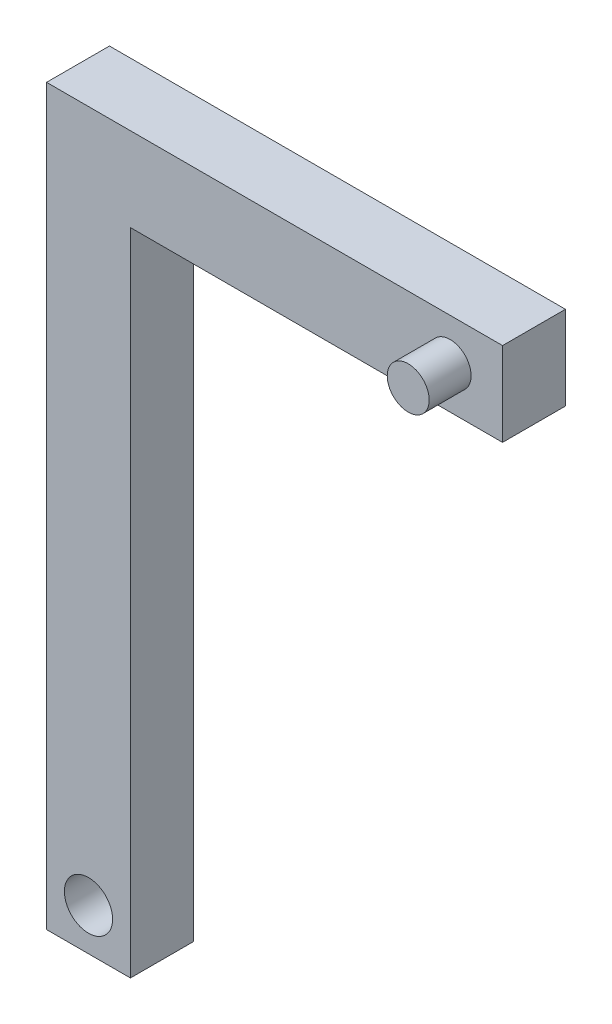
SolidWorks part; units mm, degrees
ref_plane "Alzado" through (0, 0, 0) normal (0, 0, 1) x (1, 0, 0)
ref_plane "Planta" through (0, 0, 0) normal (0, 1, 0) x (1, 0, 0)
ref_plane "Vista lateral" through (0, 0, 0) normal (1, 0, 0) x (0, 0, -1)
sketch "Croquis1" plane through (0, 0, 0) normal (0, 0, 1) x (1, 0, 0)
  line L1 (0, 0) -> (22.5, 0)
  line L2 (0, 0) -> (0, -4)
  line L3 (0, -4) -> (22.5, -4)
  line L4 (22.5, 0) -> (22.5, -4)
  circle A0 centre (3.5, -2) radius 1.05
  dimension "D5" = 2.1
  dimension "D1" = 4
  dimension "D2" = 22.5
  dimension "D3" = 19
  dimension "D4" = 2
extrude "Saliente-Extruir1" add sketch "Croquis1" along normal blind 3 contours L1 L4 L3 L2
sketch "Croquis3" plane through (0, 0, 0) normal (0, 0, -1) x (-1, 0, 0)
  line L0 (0, 0) -> (0, -4) construction
  line L1 (0, 0) -> (-22.5, 0) construction
  circle A0 centre (-20, -2) radius 1
  dimension "D3" = 2
  dimension "D1" = 20
  dimension "D2" = 2
sketch "Croquis4" plane through (0, 0, 3) normal (0, 0, 1) x (1, 0, 0)
  line L0 (0, 0) -> (22.5, 0) construction
  circle A0 centre (2.25, -2) radius 1.05
  dimension "D2" = 2.1
  dimension "D3" = 2
sketch "Croquis5" plane through (0, 0, 0) normal (0, 0, -1) x (-1, 0, 0)
  line L0 (0, -4) -> (-22.5, -4) construction
  line L1 (-4.75, -4) -> (-0.75, -4)
  line L2 (-4.75, -4) -> (-4.75, -35)
  line L3 (-4.75, -35) -> (-0.75, -35)
  line L4 (-0.75, -4) -> (-0.75, -35)
  line L5 (0, 0) -> (-22.5, 0) construction
  circle A2 centre (-2.75, -33) radius 1.05
  dimension "D1" = 2
  dimension "D4" = 2.1
  dimension "D5" = 2
  dimension "D3" = 35
  dimension "D2" = 4
extrude "Saliente-Extruir3" add sketch "Croquis5" against normal blind 3
sketch "Croquis10" plane through (0, 0, 3) normal (0, 0, 1) x (1, 0, 0)
  line L1 (0.75, -4) -> (-0.4142, -4)
  line L2 (0.75, -4) -> (0.75, 0.5775)
  line L3 (0.75, 0.5775) -> (-0.4142, 0.5775)
  line L4 (-0.4142, -4) -> (-0.4142, 0.5775)
extrude "Cortar-Extruir4" cut sketch "Croquis10" against normal through all
extrude "Saliente-Extruir4" add sketch "Croquis3" against normal blind 5
sketch "Croquis11" plane through (0, 0, 0) normal (0, 0, -1) x (-1, 0, 0)
  circle A0 centre (-2.75, -33) radius 1.15
  dimension "D1" = 2.3
extrude "Cortar-Extruir5" cut sketch "Croquis11" against normal through all
